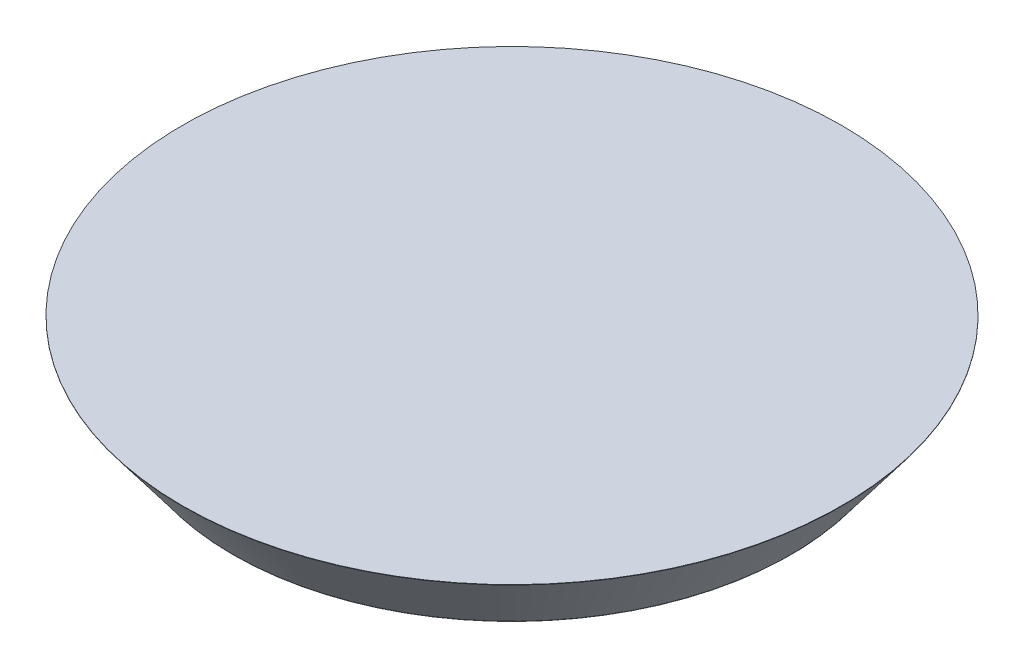
SolidWorks part; units mm, degrees
material "2"
ref_plane "Front Plane" through (0, 0, 0) normal (0, 0, 1) x (1, 0, 0)
ref_plane "Top Plane" through (0, 0, 0) normal (0, 1, 0) x (1, 0, 0)
ref_plane "Right Plane" through (0, 0, 0) normal (1, 0, 0) x (0, 0, -1)
sketch "Sketch1" plane through (0, 0, 0) normal (0, 1, 0) x (1, 0, 0)
  circle A0 centre (0, 0) radius 48.8061
  dimension "D1" = 97.6122
extrude "Extrude1" add sketch "Sketch1" along normal mid plane 13.0048
ref_plane "Plane1" through (0, -6.5024, 0) normal (0, -1, 0) x (1, 0, 0)
sketch "Sketch3" plane through (0, 0, 0) normal (0, 0, 1) x (1, 0, 0)
  line L0 (0, 0) -> (0, 10.7442)
ref_plane "Plane2" through (0, -6.5024, 0) normal (0, -1, 0) x (1, 0, 0)
sketch "Sketch4" plane through (0, -6.5024, 0) normal (0, -1, 0) x (1, 0, 0)
  point P0 (0, 0)
chamfer "Chamfer2" distance 7.5006 angle 53 1 edges at (0, -6.5024, 48.8061)
sketch "Sketch6" plane through (0, -6.5024, 0) normal (0, -1, 0) x (1, 0, 0)
  circle A0 centre (0, 0) radius 41.3055
  dimension "D1" = 82.611
extrude "Extrude-Thin2" add sketch "Sketch6" along normal blind 0.0254 thin thin type one direction reverse wall 0.508
sketch "Sketch7" plane through (0, 0, 0) normal (1, 0, 0) x (0, 0, -1)
  line L0 (-48.8061, 6.5024) -> (-48.8061, 3.4513) construction
  line L1 (48.8061, 6.5024) -> (-48.8061, 6.5024)
  line L2 (48.8061, 6.5024) -> (48.8061, 3.5052)
  line L3 (48.8061, 3.5052) -> (-48.8061, 3.5052)
  line L4 (-48.8061, 6.5024) -> (-48.8061, 3.5052)
  dimension "D1" = 2.9972
extrude "Cut-Extrude1" cut sketch "Sketch7" against normal through all and the other way through all
